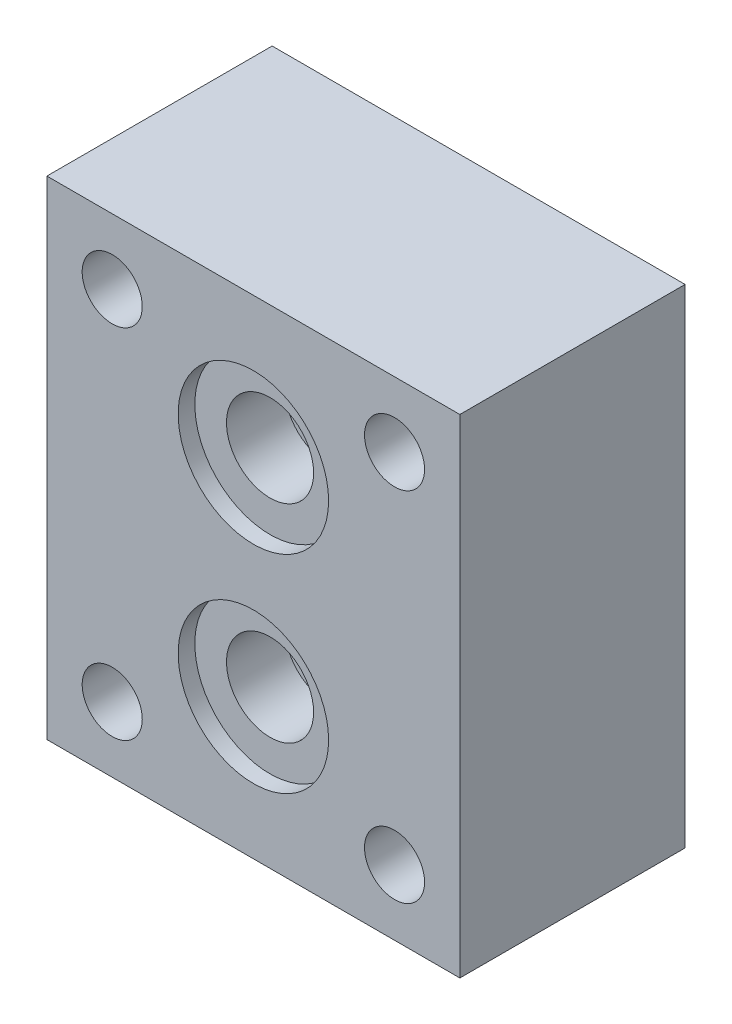
SolidWorks part; units mm, degrees
ref_plane "Front Plane" through (0, 0, 0) normal (1, 0, 0) x (0, 1, 0)
ref_plane "Top Plane" through (0, 0, 0) normal (0, 0, 1) x (0, 1, 0)
ref_plane "Right Plane" through (0, 0, 0) normal (0, 1, 0) x (-1, 0, 0)
sketch "Sketch1" plane through (0, 0, 0) normal (0, 0, 1) x (0, 1, 0)
  line L1 (-41.275, -34.925) -> (41.275, -34.925)
  line L2 (-41.275, -34.925) -> (-41.275, 34.925)
  line L3 (-41.275, 34.925) -> (41.275, 34.925)
  line L4 (41.275, -34.925) -> (41.275, 34.925)
  line L5 (-41.275, -34.925) -> (41.275, 34.925) construction
  line L6 (-41.275, 34.925) -> (41.275, -34.925) construction
  point P0 (0, 0)
extrude "Boss-Extrude1" add sketch "Sketch1" along normal mid plane 38.1
sketch "Sketch2" plane through (0, 0, 0) normal (0, 0, 1) x (0, 1, 0)
  circle A0 centre (-30.226, -23.876) radius 5.08
  circle A1 centre (30.226, -23.876) radius 5.08
  circle A2 centre (-30.226, 23.876) radius 5.08
  circle A3 centre (30.226, 23.876) radius 5.08
extrude "Cut-Extrude2" cut sketch "Sketch2" against normal through all from offset 19.05
sketch "Sketch3" plane through (0, 0, 0) normal (0, 0, 1) x (0, 1, 0)
  circle A0 centre (-17.526, 0) radius 7.366
  circle A1 centre (17.526, 0) radius 7.366
extrude "Cut-Extrude4" cut sketch "Sketch3" against normal blind 12.7 from offset 19.05
sketch "Sketch4" plane through (0, 0, 0) normal (0, 0, 1) x (0, 1, 0)
  circle A0 centre (-17.526, 0) radius 12.7254
  circle A1 centre (17.526, 0) radius 12.7254
extrude "Cut-Extrude6" cut sketch "Sketch4" against normal blind 2.8194 from offset 19.05
